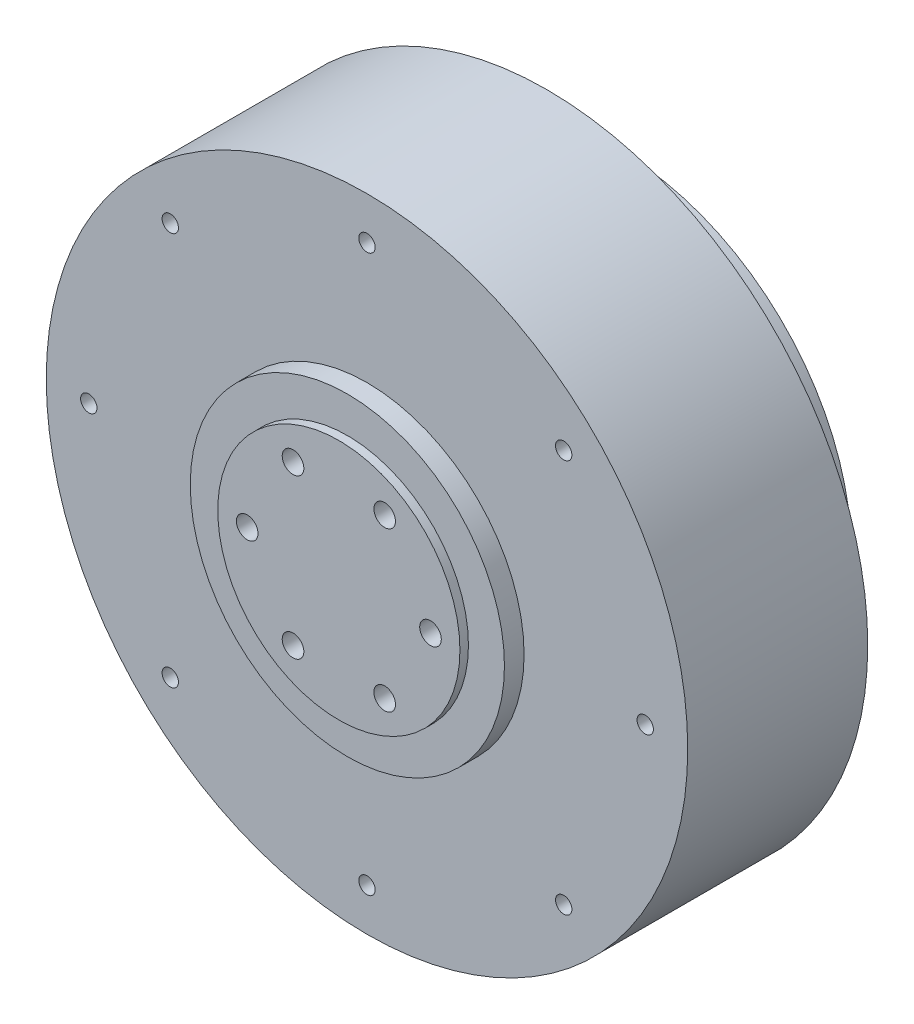
SolidWorks part; units mm, degrees
ref_plane "Front Plane" through (0, 0, 0) normal (0, 0, 1) x (1, 0, 0)
ref_plane "Top Plane" through (0, 0, 0) normal (0, 1, 0) x (1, 0, 0)
ref_plane "Right Plane" through (0, 0, 0) normal (1, 0, 0) x (0, 0, -1)
sketch "Sketch1" plane through (0, 0, 0) normal (1, 0, 0) x (0, 0, -1)
  line L0 (0, 0) -> (0, 18.5)
  line L1 (0, 18.5) -> (1.3, 18.5)
  line L2 (1.3, 18.5) -> (1.3, 24)
  line L3 (1.3, 24) -> (4.3, 24)
  line L4 (4.3, 24) -> (4.3, 49)
  line L5 (4.3, 49) -> (31.8, 49)
  line L6 (31.8, 49) -> (31.8, 35.5)
  line L7 (31.8, 35.5) -> (42.8, 35.5)
  line L8 (42.8, 35.5) -> (42.8, 0)
  line L9 (-42.7707, 0) -> (85.5811, 0) construction
  line L10 (0, 0) -> (42.8, 0)
  dimension "D1" = 18.5
  dimension "D2" = 1.3
  dimension "D3" = 5.5
  dimension "D4" = 3
  dimension "D5" = 25
  dimension "D6" = 27.5
  dimension "D7" = 11
  dimension "D8" = 35.5
  dimension "D9" = 42.8
revolve "Revolve1" add sketch "Sketch1" angle 360 about L9
hole_wizard "M4 Tapped Hole1" positions "Sketch2" profile "Sketch3" tap size "M4" standard "ISO"
sketch "Sketch2" plane through (0, 0, 0) normal (0, 0, 1) x (1, 0, 0)
  line L0 (0, 0) -> (-14, 0) construction
  circle A0 centre (0, 0) radius 14 construction
  point P0 (-14, 0)
  point P14 (-7, 12.1244)
  point P15 (7, 12.1244)
  point P16 (14, 0)
  point P17 (7, -12.1244)
  point P18 (-7, -12.1244)
  dimension "D1" = 28
  dimension "D3" = 14
  dimension "D4" = 60
  dimension "D2" = 6
sketch "Sketch3" plane through (-14, 0, 0) normal (1, 0, 0) x (0, -1, 0)
  line L0 (0, 0) -> (0, 5.9914)
  line L1 (0, 5.9914) -> (1.65, 5)
  line L2 (1.65, 5) -> (1.65, 0)
  line L5 (1.65, 0) -> (0, 0)
  line L10 (0, 5.9914) -> (-1.65, 5) construction
  line L11 (0, -6.35) -> (0, 107.95) construction
  dimension "Tap Drill Dia." = 3.3
  dimension "Tap Drill Depth" = 5
  dimension "Drill Angle" = 118
cosmetic thread "Hole Thread1" parameters "D1"=8, "D2"=4
cosmetic thread "Hole Thread2" parameters "D1"=8, "D2"=4
cosmetic thread "Hole Thread3" parameters "D1"=8, "D2"=4
cosmetic thread "Hole Thread4" parameters "D1"=8, "D2"=4
cosmetic thread "Hole Thread5" parameters "D1"=8, "D2"=4
cosmetic thread "Hole Thread6" parameters "D1"=8, "D2"=4
hole_wizard "M3 Tapped Hole1" positions "Sketch4" profile "Sketch5" tap size "M3" standard "ISO"
sketch "Sketch4" plane through (0, 0, -4.3) normal (0, 0, 1) x (1, 0, 0)
  line L0 (0, 0) -> (-42.5, 0) construction
  line L2 (0, 0) -> (-42.5, 0) construction
  circle A0 centre (0, 0) radius 42.5 construction
  point P0 (-42.5, 0)
  point P17 (-30.052, 30.052)
  point P18 (0, 42.5)
  point P19 (30.052, 30.052)
  point P20 (42.5, 0)
  point P21 (30.052, -30.052)
  point P22 (0, -42.5)
  point P23 (-30.052, -30.052)
  dimension "D1" = 85
  dimension "D3" = 42.5
  dimension "D4" = 45
  dimension "D2" = 8
sketch "Sketch5" plane through (-42.5, 0, -4.3) normal (1, 0, 0) x (0, -1, 0)
  line L0 (0, 0) -> (0, 3.7511)
  line L1 (0, 3.7511) -> (1.25, 3)
  line L2 (1.25, 3) -> (1.25, 0)
  line L5 (1.25, 0) -> (0, 0)
  line L10 (0, 3.7511) -> (-1.25, 3) construction
  line L11 (0, -6.35) -> (0, 107.95) construction
  dimension "Tap Drill Dia." = 2.5
  dimension "Tap Drill Depth" = 3
  dimension "Drill Angle" = 118
cosmetic thread "Hole Thread7" parameters "D1"=6, "D2"=3
cosmetic thread "Hole Thread8" parameters "D1"=6, "D2"=3
cosmetic thread "Hole Thread9" parameters "D1"=6, "D2"=3
cosmetic thread "Hole Thread10" parameters "D1"=6, "D2"=3
cosmetic thread "Hole Thread11" parameters "D1"=6, "D2"=3
cosmetic thread "Hole Thread12" parameters "D1"=6, "D2"=3
cosmetic thread "Hole Thread13" parameters "D1"=6, "D2"=3
cosmetic thread "Hole Thread14" parameters "D1"=6, "D2"=3
hole_wizard "M3 Tapped Hole2" positions "Sketch7" profile "Sketch8" tap size "M3" standard "ISO"
sketch "Sketch7" plane through (0, 0, -31.8) normal (0, 0, -1) x (-1, 0, 0)
  line L0 (0, 0) -> (-42.5, 0) construction
  line L2 (0, 0) -> (-42.5, 0) construction
  circle A0 centre (0, 0) radius 42.5 construction
  point P0 (-42.5, 0)
  point P16 (-30.052, 30.052)
  point P17 (0, 42.5)
  point P18 (30.052, 30.052)
  point P19 (42.5, 0)
  point P20 (30.052, -30.052)
  point P21 (0, -42.5)
  point P22 (-30.052, -30.052)
  dimension "D1" = 85
  dimension "D3" = 42.5
  dimension "D4" = 45
  dimension "D2" = 8
sketch "Sketch8" plane through (42.5, 0, -31.8) normal (1, 0, 0) x (0, 1, 0)
  line L0 (0, 0) -> (0, 3.7511)
  line L1 (0, 3.7511) -> (1.25, 3)
  line L2 (1.25, 3) -> (1.25, 0)
  line L5 (1.25, 0) -> (0, 0)
  line L10 (0, 3.7511) -> (-1.25, 3) construction
  line L11 (0, -6.35) -> (0, 107.95) construction
  dimension "Tap Drill Dia." = 2.5
  dimension "Tap Drill Depth" = 3
  dimension "Drill Angle" = 118
cosmetic thread "Hole Thread15" parameters "D1"=6, "D2"=3
cosmetic thread "Hole Thread16" parameters "D1"=6, "D2"=3
cosmetic thread "Hole Thread17" parameters "D1"=6, "D2"=3
cosmetic thread "Hole Thread18" parameters "D1"=6, "D2"=3
cosmetic thread "Hole Thread19" parameters "D1"=6, "D2"=3
cosmetic thread "Hole Thread20" parameters "D1"=6, "D2"=3
cosmetic thread "Hole Thread21" parameters "D1"=6, "D2"=3
cosmetic thread "Hole Thread22" parameters "D1"=6, "D2"=3
